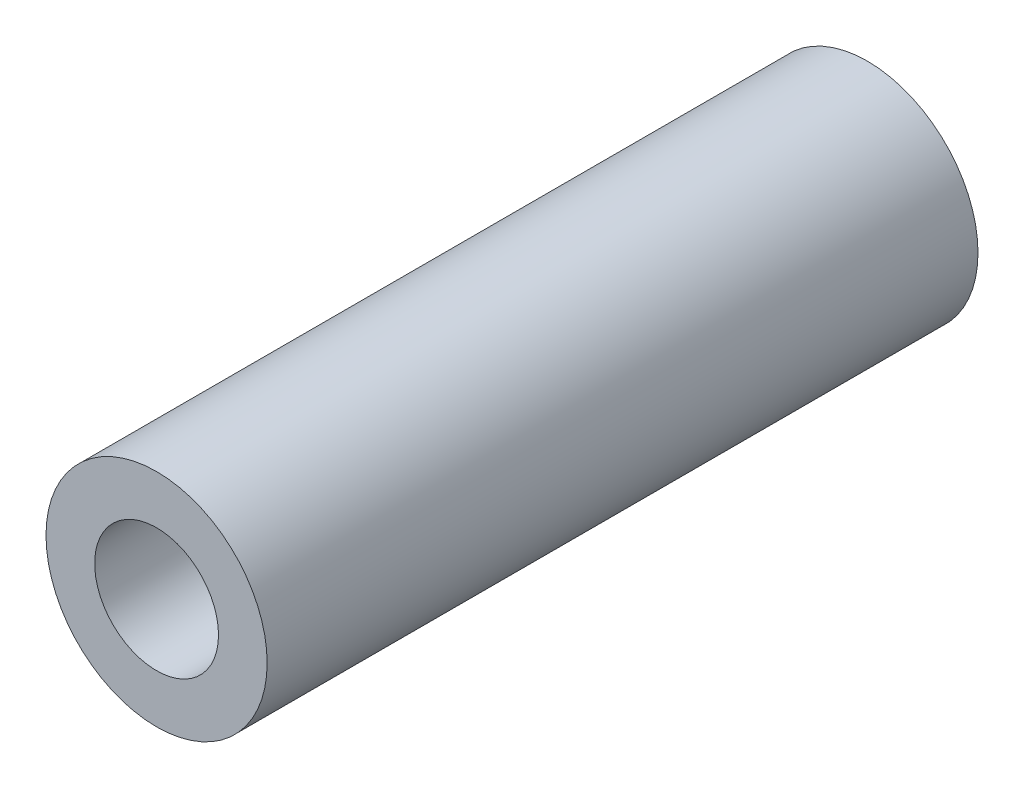
SolidWorks part; units mm, degrees
material "6061-T6 (SS)"
ref_plane "Front Plane" through (0, 0, 0) normal (0, 0, 1) x (1, 0, 0)
ref_plane "Top Plane" through (0, 0, 0) normal (0, 1, 0) x (1, 0, 0)
ref_plane "Right Plane" through (0, 0, 0) normal (1, 0, 0) x (0, 0, -1)
sketch "Sketch1" plane through (0, 0, 0) normal (1, 0, 0) x (0, 0, -1)
  line L0 (-43.4652, 0) -> (107.0331, 0) construction
  line L1 (0, 0) -> (0, 2.4892) construction
  line L2 (-14.2875, 4.445) -> (14.2875, 4.445)
  line L3 (-14.2875, 4.445) -> (-14.2875, 2.4892)
  line L4 (-14.2875, 2.4892) -> (14.2875, 2.4892)
  line L5 (14.2875, 4.445) -> (14.2875, 2.4892)
  dimension "ID" = 4.9784
  dimension "OD" = 8.89
  dimension "L" = 28.575
revolve "Revolve1" add sketch "Sketch1" angle 360 about L0
